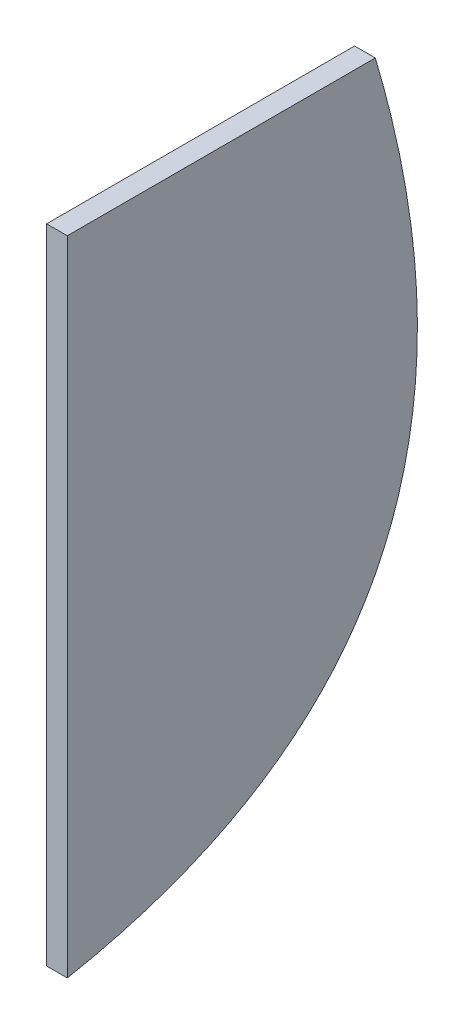
SolidWorks part; units mm, degrees
ref_plane "Front Plane" through (0, 0, 0) normal (0, 0, 1) x (1, 0, 0)
ref_plane "Top Plane" through (0, 0, 0) normal (0, 1, 0) x (1, 0, 0)
ref_plane "Right Plane" through (0, 0, 0) normal (1, 0, 0) x (0, 0, -1)
sketch "Sketch1" plane through (0, 0, 0) normal (1, 0, 0) x (0, 0, -1)
  line L0 (-376.5918, -103.8735) -> (-376.5918, -621.1265)
  line L1 (-376.5918, 621.1265) -> (-376.5918, -103.8735)
  line L2 (218.5652, 621.1265) -> (-376.5918, 621.1265)
  spline S0 degree 2 poles (218.5652, 621.1265) (534.6185, -449.3211) (-376.5918, -621.1265) knots 0 0 0 1 1 1
  dimension "D1" = 595.157
  dimension "D2" = 1242.253
  dimension "D3" = 725
extrude "Boss-Extrude1" add sketch "Sketch1" along normal blind 40
